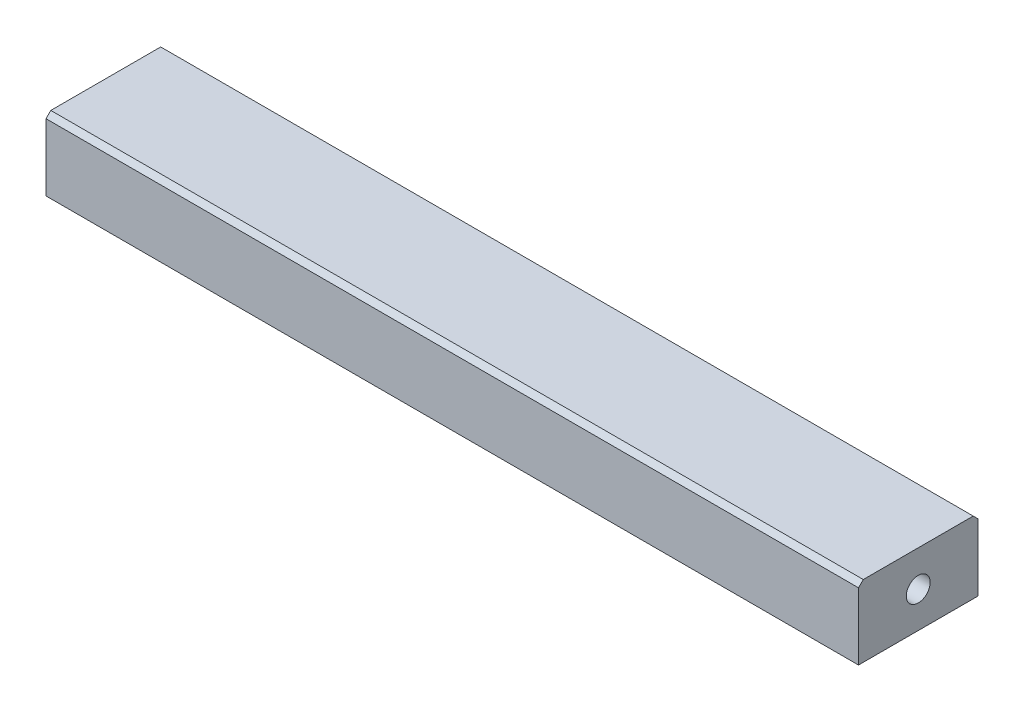
SolidWorks part; units mm, degrees
ref_plane "前视基准面" through (0, 0, 0) normal (0, 0, 1) x (1, 0, 0)
ref_plane "上视基准面" through (0, 0, 0) normal (0, 1, 0) x (1, 0, 0)
ref_plane "右视基准面" through (0, 0, 0) normal (1, 0, 0) x (0, 0, -1)
sketch "草图1" plane through (0, 0, 0) normal (0, 0, 1) x (1, 0, 0)
  line L1 (42.5, -3.75) -> (-42.5, -3.75)
  line L2 (42.5, -3.75) -> (42.5, 3.75)
  line L3 (42.5, 3.75) -> (-42.5, 3.75)
  line L4 (-42.5, -3.75) -> (-42.5, 3.75)
  line L5 (42.5, -3.75) -> (-42.5, 3.75) construction
  line L6 (42.5, 3.75) -> (-42.5, -3.75) construction
  point P0 (0, 0)
  dimension "D1" = 85
  dimension "D2" = 7.5
extrude "凸台-拉伸1" add sketch "草图1" along normal blind 12.5
sketch "草图2" plane through (42.5, 0, 0) normal (1, 0, 0) x (0, 0, -1)
  line L0 (-6.25, 3.75) -> (-6.25, -3.75) construction
  line L1 (-12.5, 3.75) -> (0, 3.75) construction
  line L2 (-12.5, -3.75) -> (0, -3.75) construction
  circle A0 centre (-6.25, 0) radius 1.25
  point P8 (0, 0)
  dimension "D1" = 2.5
extrude "切除-拉伸1" cut sketch "草图2" against normal through all
chamfer "倒角1" distance 0.5 angle 45 2 edges at (0, 3.75, 0) (0, 3.75, 12.5)
